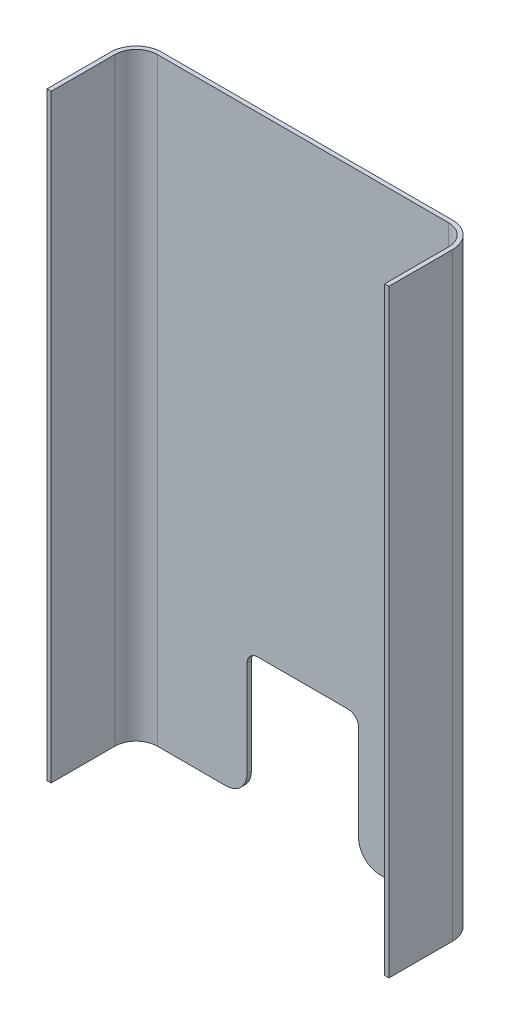
SolidWorks part; units mm, degrees
material "Polycarbonate, Black"
ref_plane "Front Plane" through (0, 0, 0) normal (0, 0, 1) x (1, 0, 0)
ref_plane "Top Plane" through (0, 0, 0) normal (0, 1, 0) x (1, 0, 0)
ref_plane "Right Plane" through (0, 0, 0) normal (1, 0, 0) x (0, 0, -1)
sketch "Sketch1" plane through (0, 0, 0) normal (0, 1, 0) x (1, 0, 0)
  line L0 (-157, -80) -> (-157, -20)
  line L1 (-137, 0) -> (137, 0)
  line L2 (157, -20) -> (157, -80)
  arc A0 (137, 0) -> (157, -20) centre (137, -20) cw
  arc A1 (-157, -20) -> (-137, 0) centre (-137, -20) cw
  dimension "D1" = 20
  dimension "D2" = 314
  dimension "D3" = 80
extrude "Extrude-Thin1" add sketch "Sketch1" along normal blind 564 thin thin type one direction reverse wall 4
sketch "Sketch2" plane through (0, 0, -4) normal (0, 0, -1) x (-1, 0, 0)
  line L0 (137, 0) -> (-137, 0) construction
  line L1 (-52.5, -140.2671) -> (52.5, -140.2671)
  line L2 (-52.5, -140.2671) -> (-52.5, 120)
  line L3 (-52.5, 120) -> (52.5, 120)
  line L4 (52.5, -140.2671) -> (52.5, 120)
  line L5 (0, 0) -> (0, 120) construction
  dimension "D1" = 120
  dimension "D2" = 105
extrude "Cut-Extrude1" cut sketch "Sketch2" against normal through all both and the other way through all
sketch "Sketch3" [suppressed] plane through (0, 0, -4) normal (0, 0, -1) x (-1, 0, 0)
  line L0 (150, 0) -> (-150, 0) construction
  line L1 (-50, 0) -> (50, 0)
  line L2 (-50, 0) -> (-50, 250)
  line L3 (-50, 250) -> (50, 250)
  line L4 (50, 0) -> (50, 250)
  dimension "D1" = 100
  dimension "D2" = 250
extrude "Cut-Extrude2" [suppressed] cut sketch "Sketch3" against normal through all both and the other way through all
fillet "Fillet1" [suppressed] radius 20
fillet "Fillet2" radius 10 2 edges at (-52.5, 120, -2) (52.5, 120, -2)
fillet "Fillet3" radius 20 2 edges at (-52.5, 0, -2) (52.5, 0, -2)
